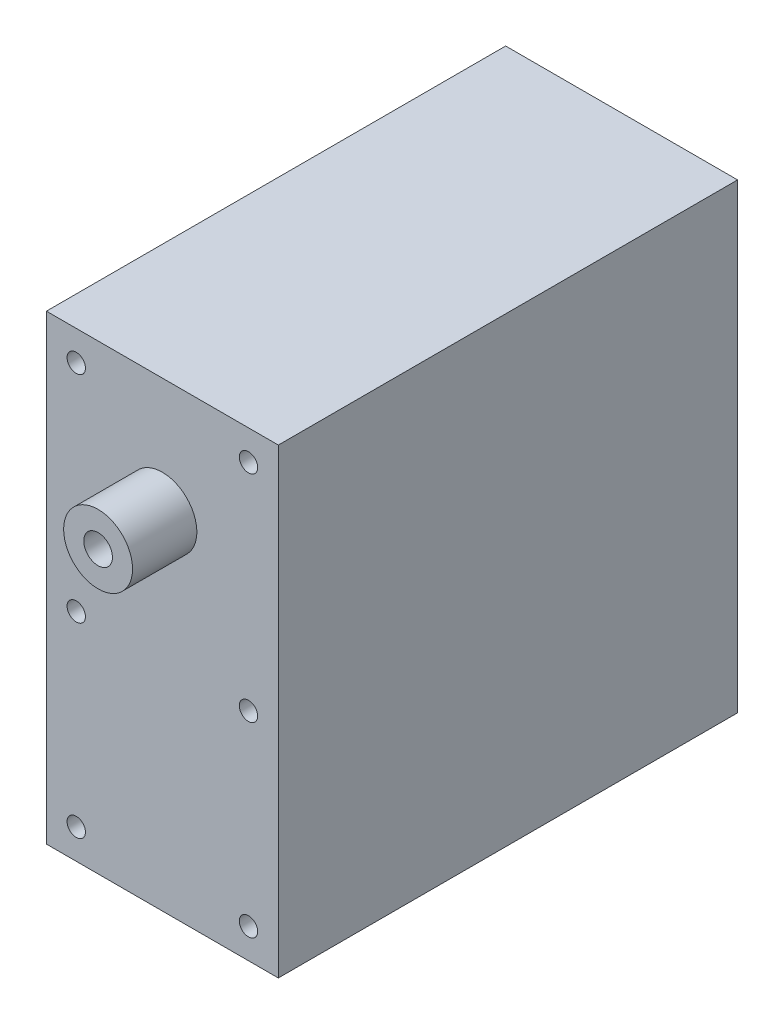
SolidWorks part; units mm, degrees
ref_plane "Front Plane" through (0, 0, 0) normal (0, 0, 1) x (1, 0, 0)
ref_plane "Top Plane" through (0, 0, 0) normal (0, 1, 0) x (1, 0, 0)
ref_plane "Right Plane" through (0, 0, 0) normal (1, 0, 0) x (0, 0, -1)
sketch "Sketch1" plane through (0, 0, 0) normal (0, 0, 1) x (1, 0, 0)
  line L1 (-10.1, -20.1) -> (10.1, -20.1)
  line L2 (-10.1, -20.1) -> (-10.1, 20.1)
  line L3 (-10.1, 20.1) -> (10.1, 20.1)
  line L4 (10.1, -20.1) -> (10.1, 20.1)
  line L5 (-10.1, -20.1) -> (10.1, 20.1) construction
  line L6 (-10.1, 20.1) -> (10.1, -20.1) construction
  point P0 (0, 0)
  dimension "D1" = 20.2
  dimension "D2" = 40.2
extrude "Boss-Extrude1" add sketch "Sketch1" along normal blind 40
ref_plane "Plane1" through (0, 0, 40) normal (0, 0, 1) x (1, 0, 0)
sketch "Sketch2" plane through (0, 0, 40) normal (0, 0, 1) x (1, 0, 0)
  line L0 (0, 20.1) -> (0, -20.1) construction
  line L1 (10.1, 20.1) -> (-10.1, 20.1) construction
  line L2 (-10.1, -20.1) -> (10.1, -20.1) construction
  line L3 (-10.1, 0) -> (10.1, 0) construction
  line L4 (-10.1, 20.1) -> (-10.1, -20.1) construction
  line L5 (10.1, -20.1) -> (10.1, 20.1) construction
  line L6 (-7.5, -1.25) -> (-7.5, 0) construction
  circle A0 centre (-7.5, -17.5) radius 0.8
  circle A1 centre (-7.5, 17.5) radius 0.8
  circle A2 centre (7.5, -17.5) radius 0.8
  circle A3 centre (7.5, 17.5) radius 0.8
  circle A4 centre (-7.5, -1.25) radius 0.8
  circle A5 centre (7.5, -1.25) radius 0.8
  dimension "D1" = 1.6
  dimension "D2" = 7.5
  dimension "D4" = 2.5
  dimension "D5" = 1.6
  dimension "D6" = 7.5
  dimension "D3" = 17.5
extrude "Cut-Extrude1" cut sketch "Sketch2" against normal blind 5
ref_plane "Plane2" through (0, 0, 40) normal (0, 0, 1) x (1, 0, 0)
sketch "Sketch3" plane through (0, 0, 40) normal (0, 0, 1) x (1, 0, 0)
  line L0 (-10.1, 0) -> (10.1, 0) construction
  line L1 (-10.1, 20.1) -> (-10.1, -20.1) construction
  line L2 (10.1, -20.1) -> (10.1, 20.1) construction
  line L3 (0, 20.1) -> (0, -20.1) construction
  line L4 (10.1, 20.1) -> (-10.1, 20.1) construction
  line L5 (-10.1, -20.1) -> (10.1, -20.1) construction
  circle A0 centre (0, 10) radius 3
  circle A1 centre (0, 10) radius 1.25
  dimension "D1" = 10
  dimension "D2" = 6
  dimension "D3" = 2.5
extrude "Boss-Extrude2" add sketch "Sketch3" along normal blind 5.6
ref_plane "Plane3" through (0, 0, 0) normal (0, 0, -1) x (-1, 0, 0)
sketch "Sketch4" plane through (0, 0, 0) normal (0, 0, -1) x (-1, 0, 0)
  line L0 (0, 20.1) -> (0, -20.1) construction
  line L1 (-10.1, 20.1) -> (10.1, 20.1) construction
  line L2 (10.1, -20.1) -> (-10.1, -20.1) construction
  line L3 (0, -20.1) -> (10.1, 0) construction
  line L4 (10.1, 20.1) -> (10.1, -20.1) construction
  line L5 (10.1, 0) -> (-10.1, 0) construction
  line L6 (-10.1, -20.1) -> (-10.1, 20.1) construction
  circle A0 centre (0, 10) radius 3
  circle A1 centre (0, 10) radius 1.5
  dimension "D1" = 10
  dimension "D2" = 6
  dimension "D3" = 3
extrude "Boss-Extrude3" add sketch "Sketch4" along normal blind 5.7
ref_plane "Plane4" through (0, 0, 0) normal (0, 0, -1) x (-1, 0, 0)
sketch "Sketch5" plane through (0, 0, 0) normal (0, 0, -1) x (-1, 0, 0)
  line L0 (0, 20.1) -> (0, -20.1) construction
  line L1 (-10.1, 20.1) -> (10.1, 20.1) construction
  line L2 (10.1, -20.1) -> (-10.1, -20.1) construction
  line L4 (-10.1, -20.1) -> (-10.1, 20.1) construction
  line L5 (-10.1, 0) -> (10.1, 0) construction
  line L6 (10.1, 20.1) -> (10.1, -20.1) construction
  circle A0 centre (0, -17.15) radius 0.8
  circle A1 centre (-7, -13.15) radius 0.8
  circle A2 centre (-7, -10.15) radius 0.8
  circle A4 centre (7, -13.15) radius 0.8
  circle A5 centre (7, -10.15) radius 0.8
  dimension "D1" = 17.15
  dimension "D2" = 1.6
  dimension "D3" = 1.6
  dimension "D4" = 7
  dimension "D5" = 13.15
  dimension "D6" = 1.6
  dimension "D7" = 7
  dimension "D8" = 10.15
extrude "Cut-Extrude2" cut sketch "Sketch5" against normal blind 5
